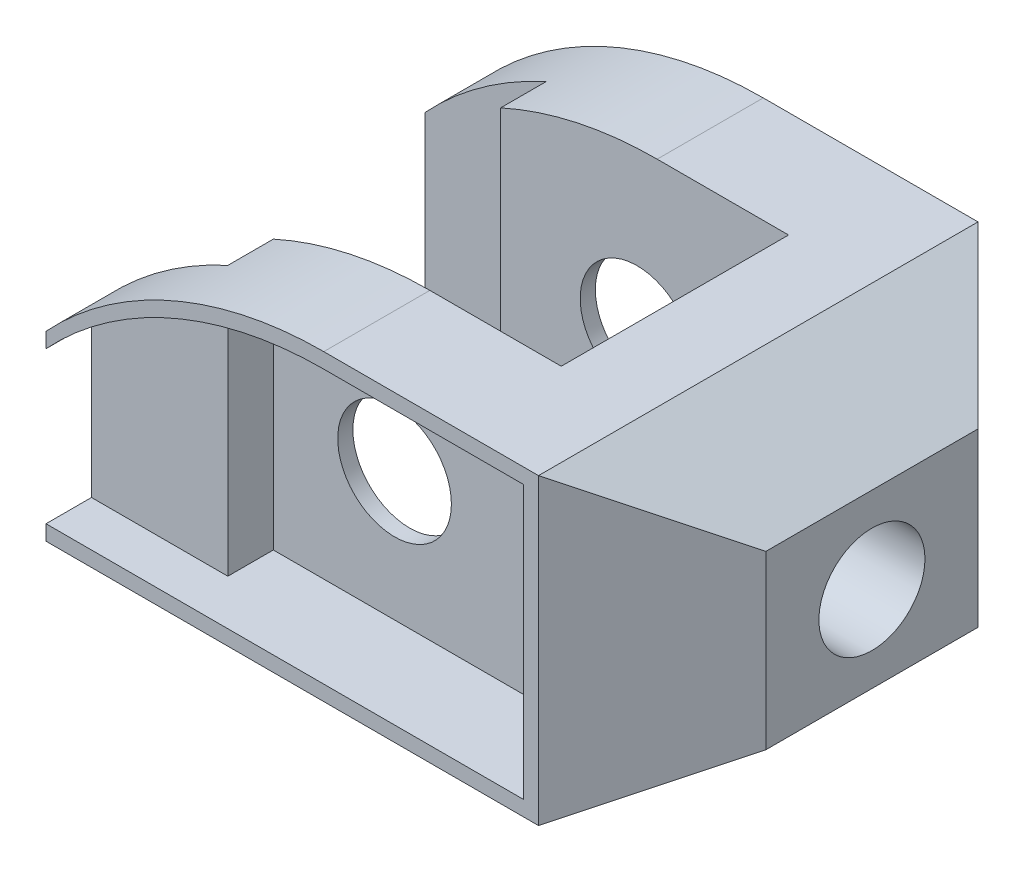
SolidWorks part; units mm, degrees
material "1060 Alloy"
ref_plane "Front Plane" through (0, 0, 0) normal (0, 0, 1) x (1, 0, 0)
ref_plane "Top Plane" through (0, 0, 0) normal (0, 1, 0) x (1, 0, 0)
ref_plane "Right Plane" through (0, 0, 0) normal (1, 0, 0) x (0, 0, -1)
sketch "Sketch1" plane through (0, 0, 0) normal (0, 1, 0) x (1, 0, 0)
  line L0 (0, 56.6723) -> (0, -56.6723) construction
  line L1 (-101.3253, 0) -> (101.3253, 0) construction
  line L3 (-40, 29) -> (40, 29)
  line L4 (-40, 29) -> (-40, -29)
  line L5 (-40, -29) -> (40, -29)
  line L6 (40, 29) -> (40, -29)
  line L7 (-40, 29) -> (40, -29) construction
  line L8 (-40, -29) -> (40, 29) construction
  point P0 (0, 0)
  point P4 (0, 0)
  point P8 (0, 0)
  dimension "D1" = 58
  dimension "D2" = 80
extrude "Boss-Extrude1" add sketch "Sketch1" along normal blind 40
sketch "Sketch2" plane through (0, 0, 29) normal (0, 0, 1) x (1, 0, 0)
  line L0 (-40, 0) -> (40, 0) construction
  line L1 (40, 40) -> (40, 0) construction
  line L2 (25, 0) -> (40, 0)
  line L3 (40, 0) -> (40, 8.6603)
  line L4 (40, 8.6603) -> (25, 0)
  line L5 (25, 40) -> (40, 40)
  line L6 (-40, 40) -> (40, 40) construction
  line L7 (40, 40) -> (40, 31.3397)
  line L8 (40, 31.3397) -> (25, 40)
  circle A0 centre (-6, 19) radius 7.5
  dimension "D1" = 19
  dimension "D3" = 15
  dimension "D2" = 46
  dimension "D4" = 15
  dimension "D5" = 30
  dimension "D6" = 15
  dimension "D7" = 30
extrude "Cut-Extrude1" cut sketch "Sketch2" against normal blind 95
sketch "Sketch4" plane through (0, 0, 29) normal (0, 0, 1) x (1, 0, 0)
  line L0 (-3.3394, 40) -> (-40, 40)
  line L1 (-40, 40) -> (-40, 24)
  line L2 (-40, 0) -> (-40, 24)
  line L3 (-40, 40) -> (-40, 0) construction
  line L4 (-40, 40) -> (25, 40) construction
  arc A1 (-3.3394, 40) -> (-40, 24) centre (-3.3394, -10) ccw
  line M5 (25, 40) -> (-40, 40)
  line M6 (-40, 40) -> (-40, 0)
  dimension "D1" = 24
  dimension "D2" = 100
extrude "Cut-Extrude4" cut sketch "Sketch4" against normal blind 95 contours A1 M5 M6
sketch "Sketch7" plane through (0, 40, 0) normal (0, 1, 0) x (1, 0, 0)
  line L0 (-47.3166, 0) -> (47.3166, 0) construction
  line L1 (25, 29) -> (25, -29)
  line L2 (25, 29) -> (40, 14)
  line L3 (40, 29) -> (40, -29) construction
  line L4 (40, 14) -> (40, 29)
  line L5 (40, 29) -> (25, 29)
  line L6 (25, -29) -> (40, -14)
  line L7 (40, -14) -> (40, -29)
  line L8 (40, -29) -> (25, -29)
  line L9 (14, 29) -> (14, -29)
  line L10 (25, 29) -> (-3.3394, 29) construction
  line L11 (-3.3394, -29) -> (25, -29) construction
  line L12 (-40, 15) -> (14, 15)
  line L13 (-40, 29) -> (-40, -29) construction
  line L14 (14, -15) -> (-40, -15)
  line L15 (-40, -29) -> (-3.3394, -29) construction
  line L16 (-3.3394, 29) -> (-40, 29) construction
  line L17 (-40, -15) -> (-40, 15)
  point P4 (0, 0)
  line M3 (-3.3394, 29) -> (-3.3394, -29)
  dimension "D1" = 45
  dimension "D2" = 45
  dimension "D3" = 11
  dimension "D4" = 14
  dimension "D5" = 14
  dimension "D6" = 14
extrude "Cut-Extrude5" cut sketch "Sketch7" against normal blind 95 contours L0 L17 L14 M3 | L17 L0 L12 M3 | L0 L9 L12 M3 | L0 L14 L9 M3 | L4 L5 L2 | L8 L7 L6
sketch "Sketch8" plane through (0, 40, 0) normal (0, 1, 0) x (1, 0, 0)
  line L0 (-40, 21) -> (-24, 21)
  line L1 (-40, 29) -> (-40, 15) construction
  line L2 (-24, 21) -> (-24, -21)
  line L3 (-24, -21) -> (-40, -21)
  line L4 (-40, -15) -> (-40, -29) construction
  line L5 (-40, -21) -> (-40, 21)
  line L6 (-40, -29) -> (-3.3394, -29) construction
  line L7 (-3.3394, 29) -> (-40, 29) construction
  dimension "D1" = 16
  dimension "D2" = 8
  dimension "D3" = 8
extrude "Cut-Extrude6" cut sketch "Sketch8" against normal blind 95
sketch "Sketch9" plane through (40, 0, 0) normal (1, 0, 0) x (0, 0, -1)
  line L0 (-29, 0) -> (-29, 40) construction
  line L2 (29, 0) -> (-29, 0) construction
  circle A0 centre (0, 20) radius 7
  dimension "D1" = 29
  dimension "D2" = 14
  dimension "D3" = 20
extrude "Cut-Extrude7" cut sketch "Sketch9" against normal blind 95
sketch "Sketch15" plane through (0, 0, 29) normal (0, 0, 1) x (1, 0, 0)
  line L0 (23, 38) -> (23, 2)
  line L1 (23, 2) -> (-22, 2)
  line L2 (-22, 2) -> (-22, 34.3873)
  line L3 (23, 38) -> (-3.3394, 38)
  line L4 (-40, 24) -> (-40, 0) construction
  line L5 (25, 0) -> (25, 40) construction
  line L6 (-3.3394, 40) -> (25, 40) construction
  line L7 (-40, 0) -> (25, 0) construction
  line L8 (-22, 2) -> (-38, 2)
  line L9 (-40, 22) -> (-40, 2)
  line L10 (-40, 2) -> (-38, 2)
  arc A0 (-3.3394, 38) -> (-40, 22) centre (-3.3394, -12) ccw
  point P11 (10.8303, 40)
  dimension "D8" = 100
  dimension "D1" = 18
  dimension "D2" = 2
  dimension "D3" = 2
  dimension "D4" = 2
  dimension "D5" = 26.3394
  dimension "D6" = 2
extrude "Cut-Extrude18" cut sketch "Sketch15" against normal blind 12 contours L3 A0 L2 L1 L0 L4
sketch "Sketch18" plane through (0, 0, 29) normal (0, 0, 1) x (1, 0, 0)
  line L0 (-22, 34.3873) -> (-22, 2)
  line L1 (-22, 2) -> (-40, 2)
  line L2 (-40, 24) -> (-40, 0) construction
  line L3 (-40, 2) -> (-40, 22)
  arc A0 (-22, 34.3873) -> (-40, 22) centre (-3.3394, -12) ccw
  dimension "D2" = 100
  dimension "D1" = 2
extrude "Cut-Extrude19" cut sketch "Sketch18" against normal blind 6
sketch "Sketch19" plane through (0, 0, -29) normal (0, 0, -1) x (-1, 0, 0)
  line L0 (-23, 38) -> (-23, 2)
  line L1 (-23, 2) -> (40, 2)
  line L2 (40, 24) -> (40, 0) construction
  line L3 (40, 2) -> (40, 22)
  line L4 (-23, 38) -> (3.3394, 38)
  line L5 (-25, 40) -> (3.3394, 40) construction
  line L6 (-25, 0) -> (-25, 40) construction
  line L7 (-25, 0) -> (40, 0) construction
  line L8 (22, 2) -> (22, 34.3873)
  arc A0 (40, 22) -> (3.3394, 38) centre (3.3394, -12) ccw
  circle M6 centre (6, 19) radius 7.5
  dimension "D6" = 100
  dimension "D1" = 2
  dimension "D2" = 2
  dimension "D3" = 2
  dimension "D4" = 2
  dimension "D5" = 26.3394
  dimension "D7" = 18
extrude "Cut-Extrude20" cut sketch "Sketch19" against normal blind 12 contours L8 A0 L4 L0 L1 M6
sketch "Sketch20" plane through (0, 0, -29) normal (0, 0, -1) x (-1, 0, 0)
  line L0 (22, 34.3873) -> (22, 2)
  line L1 (22, 2) -> (40, 2)
  line L2 (40, 24) -> (40, 0) construction
  line L3 (40, 2) -> (40, 22)
  arc A1 (40, 22) -> (22, 34.3873) centre (3.3394, -12) ccw
  dimension "D2" = 100
  dimension "D1" = 2
extrude "Cut-Extrude21" cut sketch "Sketch20" against normal blind 6
